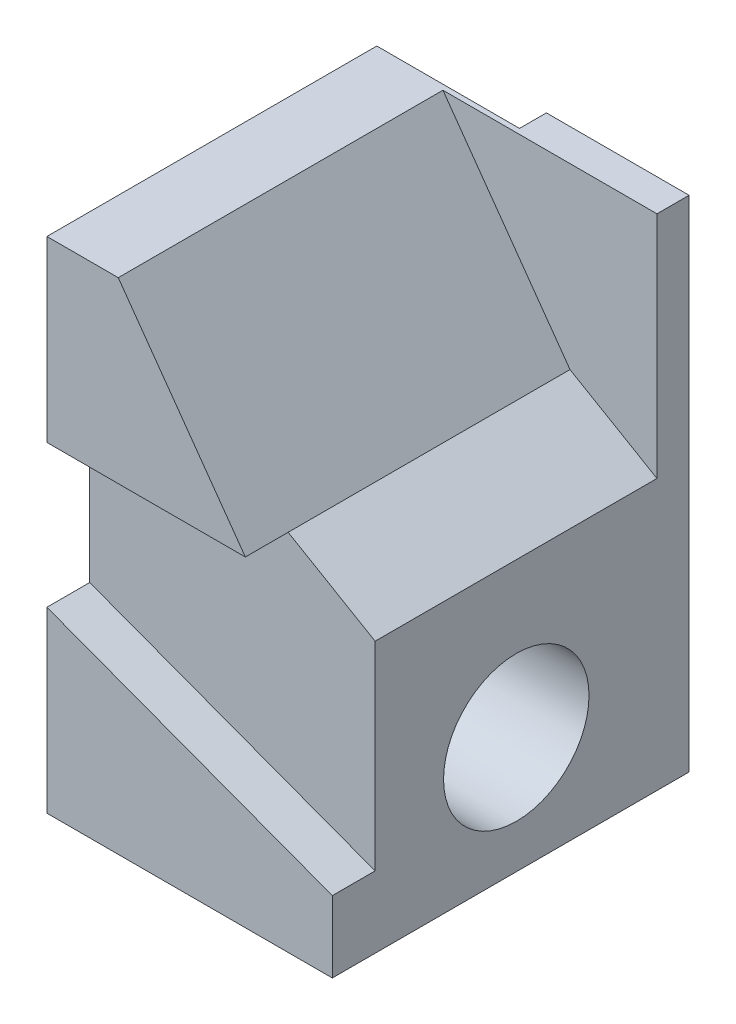
SolidWorks part; units mm, degrees
ref_plane "Alzado" through (0, 0, 0) normal (0, 0, 1) x (1, 0, 0)
ref_plane "Planta" through (0, 0, 0) normal (0, 1, 0) x (1, 0, 0)
ref_plane "Vista lateral" through (0, 0, 0) normal (1, 0, 0) x (0, 0, -1)
sketch "Croquis1" plane through (0, 0, 0) normal (0, 1, 0) x (1, 0, 0)
  line L1 (-40, 44) -> (40, 44)
  line L2 (-40, 44) -> (-40, -44)
  line L3 (-40, -44) -> (40, -44)
  line L4 (40, 44) -> (40, -44)
  line L5 (-40, 44) -> (40, -44) construction
  line L6 (-40, -44) -> (40, 44) construction
  point P0 (0, 0)
  dimension "D1" = 88
  dimension "D2" = 80
extrude "Saliente-Extruir2" add sketch "Croquis1" along normal blind 50
sketch "Croquis3" plane through (0, 0, 44) normal (0, 0, 1) x (1, 0, 0)
  line L0 (40, 0) -> (40, 20)
  line L1 (40, 50) -> (40, 0) construction
  line L2 (-40, 50) -> (40, 20)
  line L3 (-40, 50) -> (-40, 0)
  line L4 (-40, 0) -> (40, 0)
extrude "Saliente-Extruir3" add sketch "Croquis3" along normal blind 12
sketch "Croquis4" plane through (0, 50, 0) normal (0, 1, 0) x (1, 0, 0)
  line L0 (-40, -44) -> (-40, 36.4646)
  line L1 (-40, 44) -> (-40, -44) construction
  line L2 (-40, 36.4646) -> (-20, 36.4646)
  line L3 (-20, 36.4646) -> (0, 36.4646)
  line L4 (0, 36.4646) -> (0, 44)
  line L5 (40, 44) -> (-40, 44) construction
  line L6 (0, 44) -> (40, 44)
  line L7 (40, 44) -> (40, -44)
  line L8 (40, -44) -> (-40, -44)
extrude "Saliente-Extruir4" add sketch "Croquis4" along normal blind 90
sketch "Croquis5" plane through (0, 140, 0) normal (0, 1, 0) x (1, 0, 0)
  line L1 (0, 36.4646) -> (-40, 36.4646) construction
  line L2 (-20, 36.4646) -> (-20, -44)
  line L3 (40, -44) -> (-40, -44) construction
  line L4 (-20, -44) -> (-20.0005, -43.86)
  line L7 (-40, 36.4646) -> (-40, -44)
sketch "Croquis6" plane through (0, 0, 44) normal (0, 0, 1) x (1, 0, 0)
  line L0 (-40, 140) -> (-40, 90)
  line L1 (-40, 140) -> (-40, 50) construction
  line L2 (-20.0002, 140) -> (15.6192, 90)
  line L3 (-20, 140) -> (-20.0005, 140) construction
  line L4 (-40, 90) -> (15.6192, 90)
  line L5 (-40, 140) -> (-20.0002, 140)
extrude "Saliente-Extruir5" add sketch "Croquis6" along normal blind 12
sketch "Croquis7" plane through (0, 0, 44) normal (0, 0, 1) x (1, 0, 0)
  line L0 (-20.0002, 140) -> (40, 140)
  line L1 (-20, 140) -> (-20.0005, 140) construction
  line L2 (-20.0002, 140) -> (15.6192, 90)
  line L3 (15.6192, 90) -> (40, 90)
  line L4 (40, 140) -> (40, 20) construction
  line L5 (40, 90) -> (40, 140)
extrude "Cortar-Extruir1" cut sketch "Croquis7" against normal blind 79
sketch "Croquis8" plane through (40, 0, 0) normal (1, 0, 0) x (0, 0, -1)
  line L0 (35, 90) -> (35, 61.9077)
  line L3 (-44, 90) -> (-44, 20) construction
  line L4 (-44, 60.1404) -> (-44, 90)
  line L5 (35, 90) -> (-44, 90) construction
  line L6 (-44, 90) -> (35, 90)
  line L9 (-44, 60.1404) -> (35, 61.9077)
extrude "Cortar-Extruir3" cut sketch "Croquis8" against normal blind 34
sketch "Croquis10" plane through (0, 0, -35) normal (0, 0, 1) x (1, 0, 0)
  line L0 (15.6192, 90) -> (40, 61.9077)
  line L1 (40, 61.9077) -> (6, 61.9077)
  line L2 (6, 61.9077) -> (6, 90)
  line L3 (6, 90) -> (15.6192, 90)
extrude "Saliente-Extruir6" [suppressed] add sketch "Croquis10" along normal blind 80
sketch "Croquis11" [suppressed] plane through (0, 0, -35) normal (0, 0, 1) x (1, 0, 0)
  line L5 (-20.0002, 140) -> (40, 140)
  line L6 (40, 140) -> (-20.0002, 140) construction
  line L7 (-20.0002, 140) -> (15.6192, 90) construction
  line L8 (40, 140) -> (40, 61.9077)
  line L9 (-20.0002, 140) -> (40, 61.9077)
extrude "Cortar-Extruir4" [suppressed] cut sketch "Croquis11" against normal blind 80
sketch "Croquis13" plane through (40, 0, 0) normal (1, 0, 0) x (0, 0, -1)
  circle A0 centre (-4.4381, 32.6116) radius 20.3836
extrude "Cortar-Extruir5" cut sketch "Croquis13" against normal blind 80
sketch "Croquis16" plane through (6, 0, 0) normal (1, 0, 0) x (0, 0, -1)
  line L0 (-44, 90) -> (35, 90)
  line L1 (35, 90) -> (35, 61.9077)
  line L2 (35, 61.9077) -> (35, 90) construction
  line L3 (-44, 60.1404) -> (35, 61.9077) construction
  line L4 (35, 61.9077) -> (-44, 60.1404)
  line L5 (-44, 60.1404) -> (-44, 90)
extrude "Saliente-Extruir8" add sketch "Croquis16" along normal blind 34
sketch "Croquis17" plane through (0, 0, 44) normal (0, 0, 1) x (1, 0, 0)
  line L0 (15.6192, 90) -> (40, 75.7596)
  line L1 (40, 90) -> (40, 20) construction
  line L2 (40, 75.7596) -> (40, 90)
  line L3 (40, 90) -> (15.6192, 90)
extrude "Cortar-Extruir7" cut sketch "Croquis17" against normal blind 79
